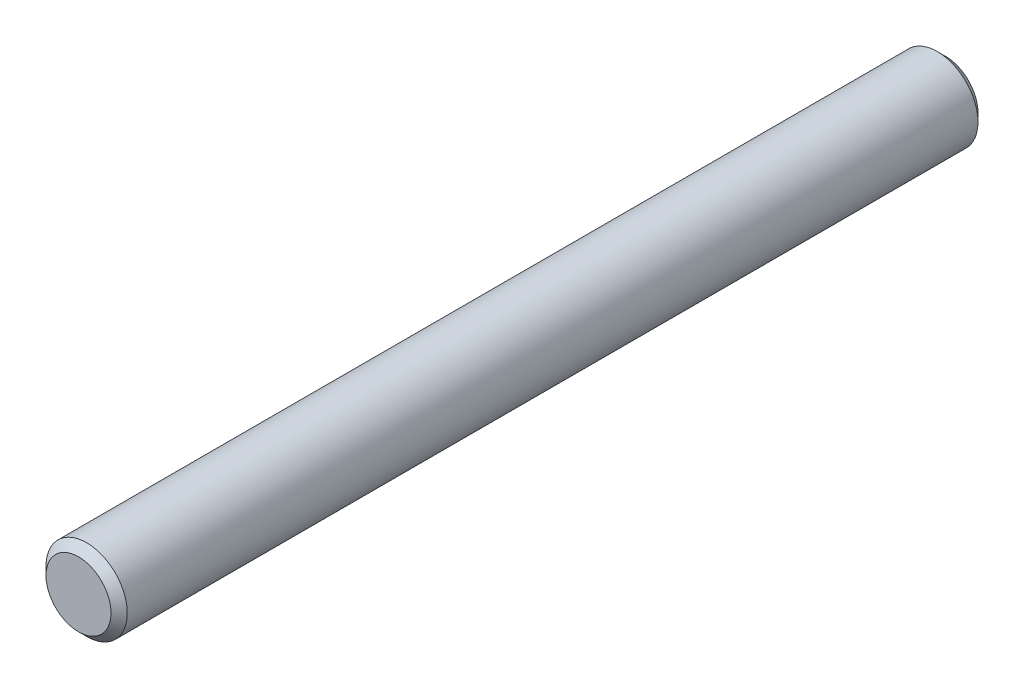
SolidWorks part; units mm, degrees
ref_plane "Front Plane" through (0, 0, 0) normal (0, 0, 1) x (1, 0, 0)
ref_plane "Top Plane" through (0, 0, 0) normal (0, 1, 0) x (1, 0, 0)
ref_plane "Right Plane" through (0, 0, 0) normal (1, 0, 0) x (0, 0, -1)
sketch "Sketch1" plane through (0, 0, 0) normal (0, 0, 1) x (1, 0, 0)
  line L0 (-2.3813, 0) -> (2.3813, 0) construction
  circle A0 centre (0, 0) radius 2.3813 construction
  point P3 (-2.3813, 0)
  point P4 (2.3813, 0)
  point P7 (0, 2.3813)
  point P8 (0, -2.3813)
  dimension "Diameter" = 4.7625
sketch "Sketch2" plane through (0, 0, 0) normal (1, 0, 0) x (0, 0, -1)
  line L0 (25.4, 0) -> (-25.4, 0) construction
  line L1 (-25.4, 2.3813) -> (-25.4, -2.3813) construction
  line L2 (25.4, 2.3813) -> (25.4, -2.3813) construction
  point P0 (-23.368, 0)
  point P4 (0, 0)
  point P8 (-25.4, 0)
  point P11 (25.4, 0)
  point P13 (23.368, 0)
  dimension "Length" = 50.8
  dimension "D1" = 2.032
  dimension "D2" = 2.032
sketch "Sketch3" plane through (0, 0, 0) normal (0, 0, 1) x (1, 0, 0)
  circle A0 centre (0, 0) radius 2.3813 construction
  circle A1 centre (0, 0) radius 2.3813
extrude "Boss-Extrude1" add sketch "Sketch3" along normal up to vertex (25.4 mm away) and the other way up to vertex (25.4 mm away) up to point (0, 0, 25.4) other way up to point (0, 0, -25.4)
chamfer "Chamfer1" distance 0.4763 angle 45 2 edges at (2.3813, 0, -25.4) (2.3813, 0, 25.4)
equation "\"D2@Sketch2\"=\"D1@Sketch2\""
equation "\"D1@Sketch2\"=\"Length@Sketch2\"*.04"
equation "\"D1@Chamfer1\"=\"Diameter@Sketch1\"*.1"
